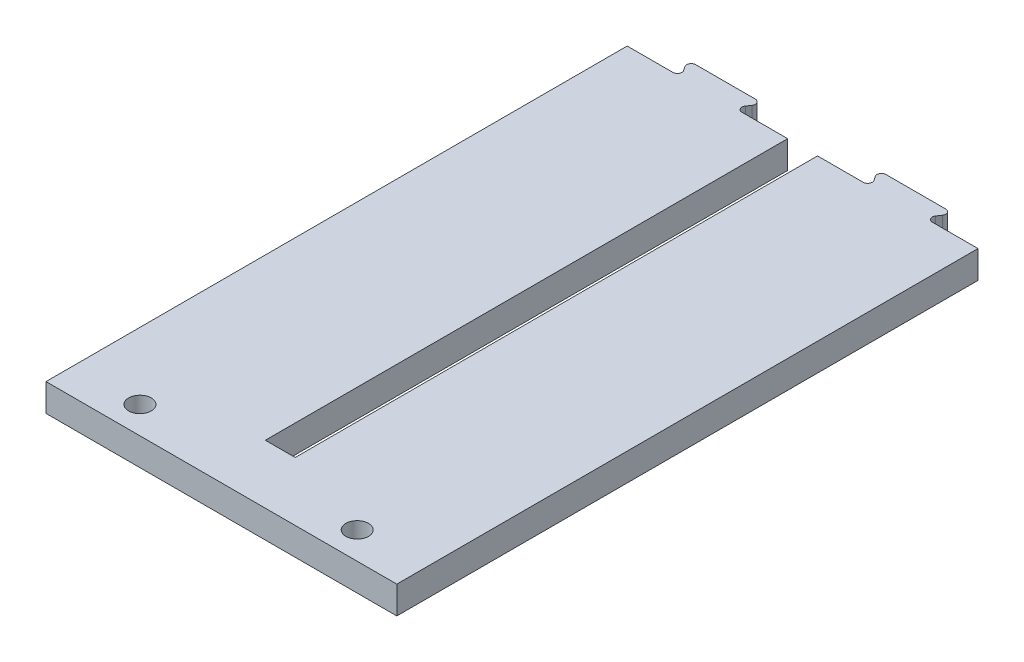
SolidWorks part; units mm, degrees
ref_plane "Front Plane" through (0, 0, 0) normal (0, 0, 1) x (1, 0, 0)
ref_plane "Top Plane" through (0, 0, 0) normal (0, 1, 0) x (1, 0, 0)
ref_plane "Right Plane" through (0, 0, 0) normal (1, 0, 0) x (0, 0, -1)
sketch "Sketch1" plane through (0, 0, 0) normal (0, 1, 0) x (1, 0, 0)
  line L1 (-19.375, 0) -> (19.375, 0)
  line L2 (-19.375, 0) -> (-19.375, 72.5)
  line L3 (-19.375, 72.5) -> (19.375, 72.5)
  line L4 (19.375, 0) -> (19.375, 72.5)
  point P5 (0, 0)
  dimension "D1" = 38.75
  dimension "D2" = 72.5
extrude "Boss-Extrude1" add sketch "Sketch1" along normal blind 3.05
sketch "Sketch4" plane through (0, 3.05, 0) normal (0, 1, 0) x (1, 0, 0)
  line L0 (-19.375, 72.5) -> (19.375, 72.5) construction
  line L2 (-19.375, 0) -> (19.375, 0) construction
  line L3 (1.65, 70.5) -> (-1.65, 70.5)
  line L4 (-1.65, 70.5) -> (-1.65, 69.5)
  line L5 (-1.65, 69.5) -> (1.65, 69.5)
  line L6 (1.65, 69.5) -> (1.65, 70.5)
  line L7 (0, 0) -> (0, 72.5) construction
  line L9 (1.65, 68.3) -> (-1.65, 68.3)
  line L10 (-1.65, 68.3) -> (-1.65, 6.5)
  line L11 (-1.65, 6.5) -> (1.65, 6.5)
  line L12 (1.65, 6.5) -> (1.65, 68.3)
  point P6 (0, 6.5)
  point P10 (0, 70.5)
  point P22 (0, 68.3)
  dimension "D1" = 2
  dimension "D2" = 1
  dimension "D3" = 1.2
  dimension "D4" = 3.3
  dimension "D7" = 6.5
extrude "Cut-Extrude1" cut sketch "Sketch4" against normal through all contours L5 L7 L3 L4 | L11 L7 L9 L10 | L7 L11 L12 L9 | L7 L5 L6 L3
sketch "Sketch8" plane through (0, 3.05, 0) normal (0, 1, 0) x (1, 0, 0)
  line L0 (19.375, 0) -> (19.375, 72.5) construction
  line L1 (-19.375, 72.5) -> (19.375, 72.5)
  line L2 (-19.375, 72.5) -> (-19.375, 64.2)
  line L3 (-19.375, 64.2) -> (19.375, 64.2)
  line L4 (19.375, 72.5) -> (19.375, 64.2)
  dimension "D1" = 8.3
extrude "Cut-Extrude5" cut sketch "Sketch8" against normal through all
sketch "Sketch9" plane through (0, 3.05, 0) normal (0, 1, 0) x (1, 0, 0)
  line L0 (-19.375, 64.2) -> (19.375, 64.2) construction
  line L1 (-19.375, 64.2) -> (-19.375, 66.2) construction
  line L2 (19.375, 64.2) -> (19.375, 66.2) construction
  line L3 (-19.375, 66.2) -> (19.375, 66.2) construction
  line L4 (-19.375, 64.2) -> (-13.375, 64.2)
  line L5 (-13.375, 64.2) -> (-14.7625, 66.2)
  line L6 (-14.7625, 66.2) -> (-6.2625, 66.2)
  line L7 (-6.2625, 66.2) -> (-7.65, 64.2)
  line L8 (-7.65, 64.2) -> (-1.65, 64.2)
  line L9 (1.65, 64.2) -> (7.65, 64.2)
  line L10 (7.65, 64.2) -> (6.2625, 66.2)
  line L11 (6.2625, 66.2) -> (14.7625, 66.2)
  line L12 (14.7625, 66.2) -> (13.375, 64.2)
  line L13 (13.375, 64.2) -> (19.375, 64.2)
  line L14 (-13.375, 64.2) -> (-7.65, 64.2)
  line L15 (7.65, 64.2) -> (13.375, 64.2)
  line L16 (-19.375, 66.2) -> (-14.7625, 66.2)
  line L17 (14.7625, 66.2) -> (19.375, 66.2)
  line M1 (-1.65, 64.2) -> (-19.375, 64.2)
  line M5 (19.375, 64.2) -> (1.65, 64.2)
  dimension "D1" = 2
  dimension "D3" = 8.5
  dimension "D4" = 6
extrude "Boss-Extrude3" add sketch "Sketch9" against normal blind 3.05 contours L7 L6 L5 M1 | L12 L11 L10 M5
fillet "Fillet2" radius 0.5 8 edges at (13.375, 1.525, -64.2) (-7.65, 1.525, -64.2) (14.7625, 1.525, -66.2) (7.65, 1.525, -64.2) (6.2625, 1.525, -66.2) (-6.2625, 1.525, -66.2) (-14.7625, 1.525, -66.2) (-13.375, 1.525, -64.2)
sketch "Hole Locations" plane through (0, 3.05, 0) normal (0, 1, 0) x (1, 0, 0)
  line L0 (-19.375, 0) -> (19.375, 0) construction
  line L4 (0, 0) -> (0, 70) construction
  circle A0 centre (-12, 3) radius 1 construction
  circle A2 centre (12, 3) radius 1 construction
  point P3 (-10.9578, 3.5)
  point P4 (-6.5425, 3.5)
  dimension "D3" = 2
  dimension "D1" = 12
  dimension "D2" = 3
hole_wizard "Tap Drill for M3x0.5 Tap1" positions "Sketch10" profile "Sketch11" hole size "M3x0.5" standard "ANSI Metric" end condition through all
sketch "Sketch10" plane through (0, 3.05, 0) normal (0, 1, 0) x (1, 0, 0)
  point P0 (-12, 3)
  point P3 (12, 3)
sketch "Sketch11" plane through (-12, 3.05, -3) normal (1, 0, 0) x (0, 0, 1)
  line L0 (0, 0) -> (0, 3.05)
  line L1 (0, 3.05) -> (1.25, 3.05)
  line L2 (1.25, 3.05) -> (1.25, 0)
  line L5 (1.25, 0) -> (0, 0)
  line L11 (0, -6.35) -> (0, 107.95) construction
  dimension "Thru Hole Dia." = 2.5
  dimension "Thru Hole Depth" = 3.05
